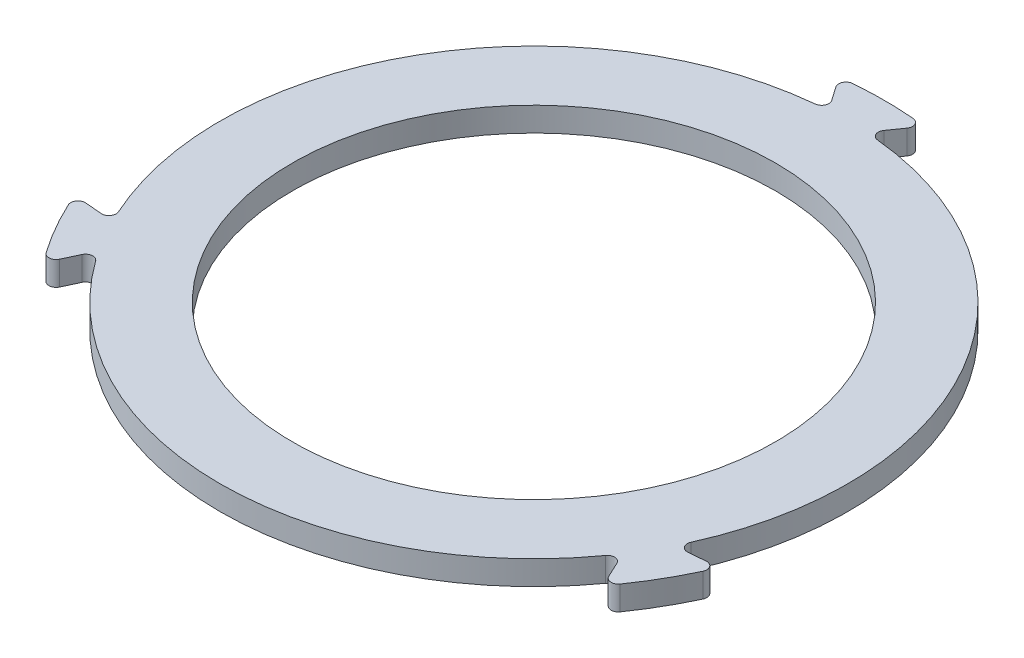
SolidWorks part; units mm, degrees
ref_plane "Front Plane" through (0, 0, 0) normal (0, 0, 1) x (1, 0, 0)
ref_plane "Top Plane" through (0, 0, 0) normal (0, 1, 0) x (1, 0, 0)
ref_plane "Right Plane" through (0, 0, 0) normal (1, 0, 0) x (0, 0, -1)
sketch "Sketch2" plane through (0, 0, 0) normal (1, 0, 0) x (0, 0, -1)
  line L0 (-50, 0) -> (-65, 0)
  line L1 (-65, 0) -> (-65, 5)
  line L2 (-65, 5) -> (-50, 5)
  line L5 (-50, 5) -> (-50, 0)
  point P3 (0, 0)
  point P6 (0, 0)
  point P8 (-21.7404, 0)
  point P9 (-22.787, 8.087)
  dimension "D1" = 65
  dimension "D2" = 5
  dimension "D4" = 15
ref_axis "Axis1" through (0, -0.75, 0) along (0, 1, 0)
revolve "Revolve1" add sketch "Sketch2" angle 360 about axis through (0, -0.75, 0) along (0, 1, 0)
sketch "Sketch4" plane through (0, 5, 0) normal (0, 1, 0) x (1, 0, 0)
  line L0 (0, 0) -> (0, 84.4218) construction
  line L1 (-3.8812, 64.884) -> (-8.8355, 71.9596)
  line L2 (8.8355, 71.9596) -> (3.8812, 64.884)
  line L3 (-3.8812, 64.884) -> (0, 59.3412) construction
  line L4 (0, 0) -> (-8.8355, 71.9596) construction
  arc A0 (-3.8812, 64.884) -> (3.8812, 64.884) centre (0, 0) cw
  arc A2 (-8.8355, 71.9596) -> (8.8355, 71.9596) centre (0, 0) cw
  circle A3 centre (0, 0) radius 65 construction
  dimension "D1" = 35
  dimension "D2" = 7.5
  dimension "D3" = 7
  dimension "D4" = 130
extrude "Boss-Extrude1" add sketch "Sketch4" against normal blind 5
fillet "Fillet2" radius 1.5 4 edges at (-3.8812, 2.5, -64.884) (-8.8355, 2.5, -71.9596) (8.8355, 2.5, -71.9596) (3.8812, 2.5, -64.884)
pattern_circular "CirPattern4" count 3 over 360 about axis through (0, 0, 0) along (0, 1, 0) of "Fillet2", "Boss-Extrude1"
